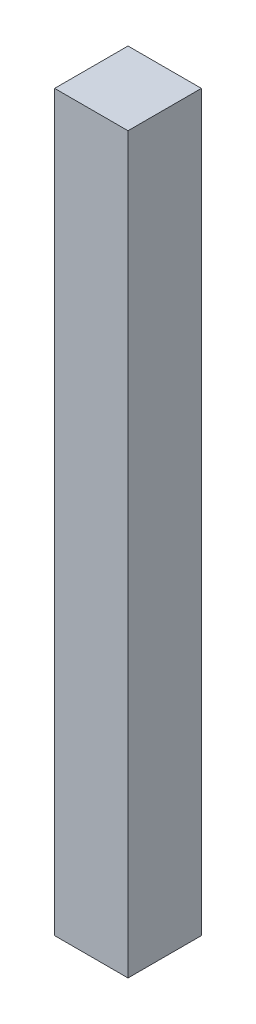
SolidWorks part; units mm, degrees
ref_plane "Front Plane" through (0, 0, 0) normal (0, 0, 1) x (1, 0, 0)
ref_plane "Top Plane" through (0, 0, 0) normal (0, 1, 0) x (1, 0, 0)
ref_plane "Right Plane" through (0, 0, 0) normal (1, 0, 0) x (0, 0, -1)
sketch "Sketch1" plane through (0, 0, 0) normal (0, 1, 0) x (1, 0, 0)
  line L1 (-25.4, -25.4) -> (25.4, -25.4)
  line L2 (-25.4, -25.4) -> (-25.4, 25.4)
  line L3 (-25.4, 25.4) -> (25.4, 25.4)
  line L4 (25.4, -25.4) -> (25.4, 25.4)
  line L5 (-25.4, -25.4) -> (25.4, 25.4) construction
  line L6 (-25.4, 25.4) -> (25.4, -25.4) construction
  point P0 (0, 0)
  dimension "D1" = 50.8
extrude "Boss-Extrude1" add sketch "Sketch1" along normal blind 508
